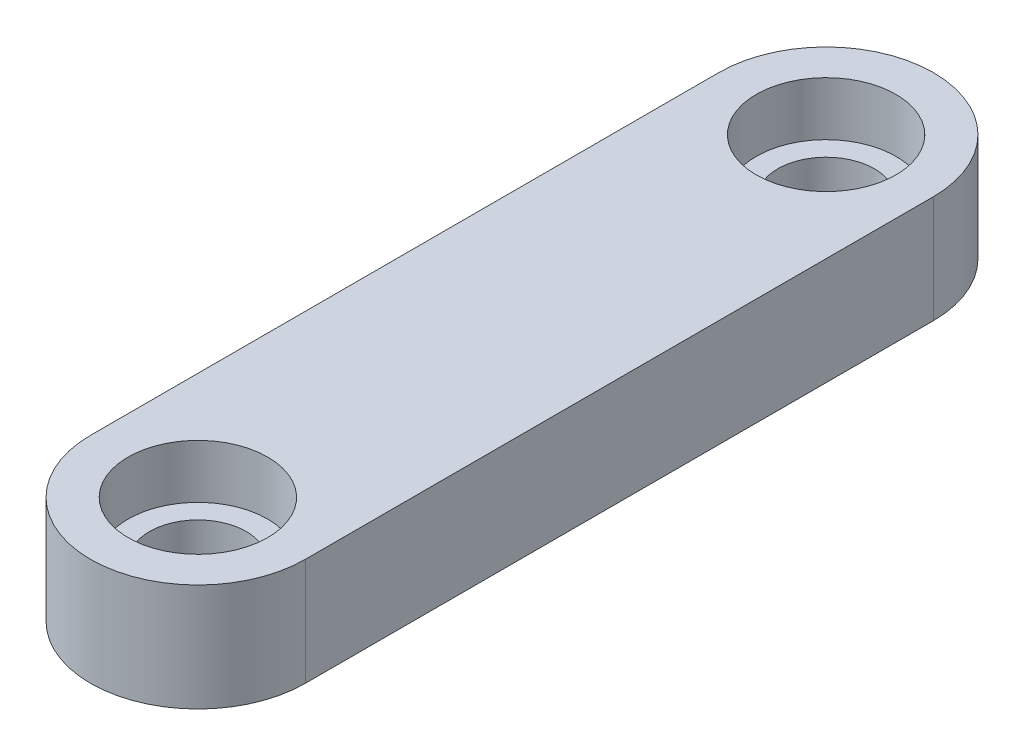
SolidWorks part; units mm, degrees
ref_plane "정면" through (0, 0, 0) normal (0, 0, 1) x (1, 0, 0)
ref_plane "윗면" through (0, 0, 0) normal (0, 1, 0) x (1, 0, 0)
ref_plane "우측면" through (0, 0, 0) normal (1, 0, 0) x (0, 0, -1)
sketch "스케치1" plane through (0, 0, 0) normal (0, 0, 1) x (1, 0, 0)
  line L1 (-10, -5) -> (10, -5)
  line L2 (-10, -5) -> (-10, 5)
  line L3 (-10, 5) -> (10, 5)
  line L4 (10, -5) -> (10, 5)
  line L5 (-10, -5) -> (10, 5) construction
  line L6 (-10, 5) -> (10, -5) construction
  point P0 (0, 0)
  dimension "D1" = 10
  dimension "D2" = 20
extrude "보스-돌출1" add sketch "스케치1" along normal blind 80.2974
sketch "스케치2" plane through (0, 5, 0) normal (0, 1, 0) x (1, 0, 0)
  circle A0 centre (0, -10.9027) radius 6.5
  dimension "D1" = 13
extrude "컷-돌출1" cut sketch "스케치2" against normal blind 5
ref_plane "평면1" through (0, 0, 40.1487) normal (0, 0, 1) x (1, 0, 0)
sketch "스케치3" plane through (0, 5, 0) normal (0, 1, 0) x (1, 0, 0)
  line L0 (-22.6352, -10.9027) -> (28.5035, -10.9027) construction
  line L1 (-21.2621, -10.9027) -> (-10, -10.9027)
  line L2 (10, -10.9027) -> (21.2621, -10.9027)
  circle A0 centre (0, -10.9027) radius 4.5
  circle A1 centre (0, -10.9027) radius 6.5
  circle A2 centre (0, -10.9027) radius 6.5 construction
  arc A3 (10, -10.9027) -> (-10, -10.9027) centre (0, -10.9027) ccw
  arc A4 (21.2621, -10.9027) -> (-21.2621, -10.9027) centre (0, -10.9027) ccw
  dimension "D2" = 9
  dimension "D1" = 0
extrude "컷-돌출2" cut sketch "스케치3" against normal blind 20
mirror "대칭 복사1" about plane through (0, 0, 40.1487) normal (0, 0, 1) of "컷-돌출2", "컷-돌출1"
